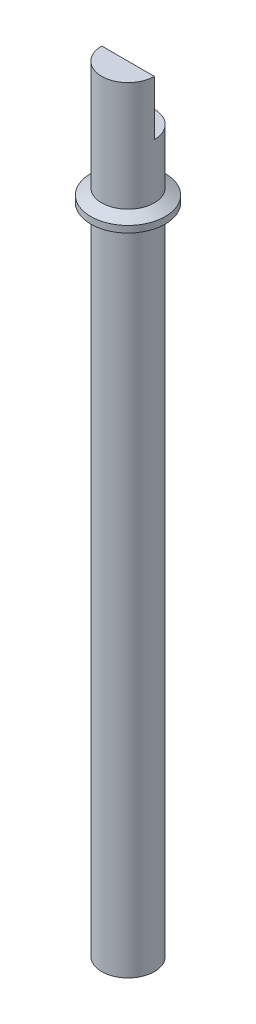
SolidWorks part; units mm, degrees
ref_plane "Front Plane" through (0, 0, 0) normal (0, 0, 1) x (1, 0, 0)
ref_plane "Top Plane" through (0, 0, 0) normal (0, 1, 0) x (1, 0, 0)
ref_plane "Right Plane" through (0, 0, 0) normal (1, 0, 0) x (0, 0, -1)
sketch "Sketch1" plane through (0, 0, 0) normal (0, 0, 1) x (1, 0, 0)
  line L0 (0, 0) -> (0, -2.5)
  line L1 (0, -2.5) -> (-0.25, -2.6443)
  line L2 (-0.25, -2.6443) -> (-0.25, -2.7943)
  line L3 (-0.25, -2.7943) -> (0, -2.9387)
  line L4 (0, -2.9387) -> (0, -17.6887)
  line L5 (0, -17.6887) -> (0.6, -17.6887)
  line L6 (0.6, -17.6887) -> (0.6, 0)
  line L7 (0.6, 0) -> (0, 0)
  dimension "D1" = 2.5
  dimension "D2" = 14.75
  dimension "D3" = 120
  dimension "D4" = 120
  dimension "D5" = 0.15
  dimension "D6" = 0.6
  dimension "D7" = 0.85
revolve "Revolve1" add sketch "Sketch1" angle 360 about L6
sketch "Sketch2" plane through (0, 0, 0) normal (0, 1, 0) x (1, 0, 0)
  line L0 (0, 0) -> (1.2, 0)
  arc A0 (1.2, 0) -> (0, 0) centre (0.6, 0) ccw
extrude "Cut-Extrude1" cut sketch "Sketch2" against normal blind 1.25
